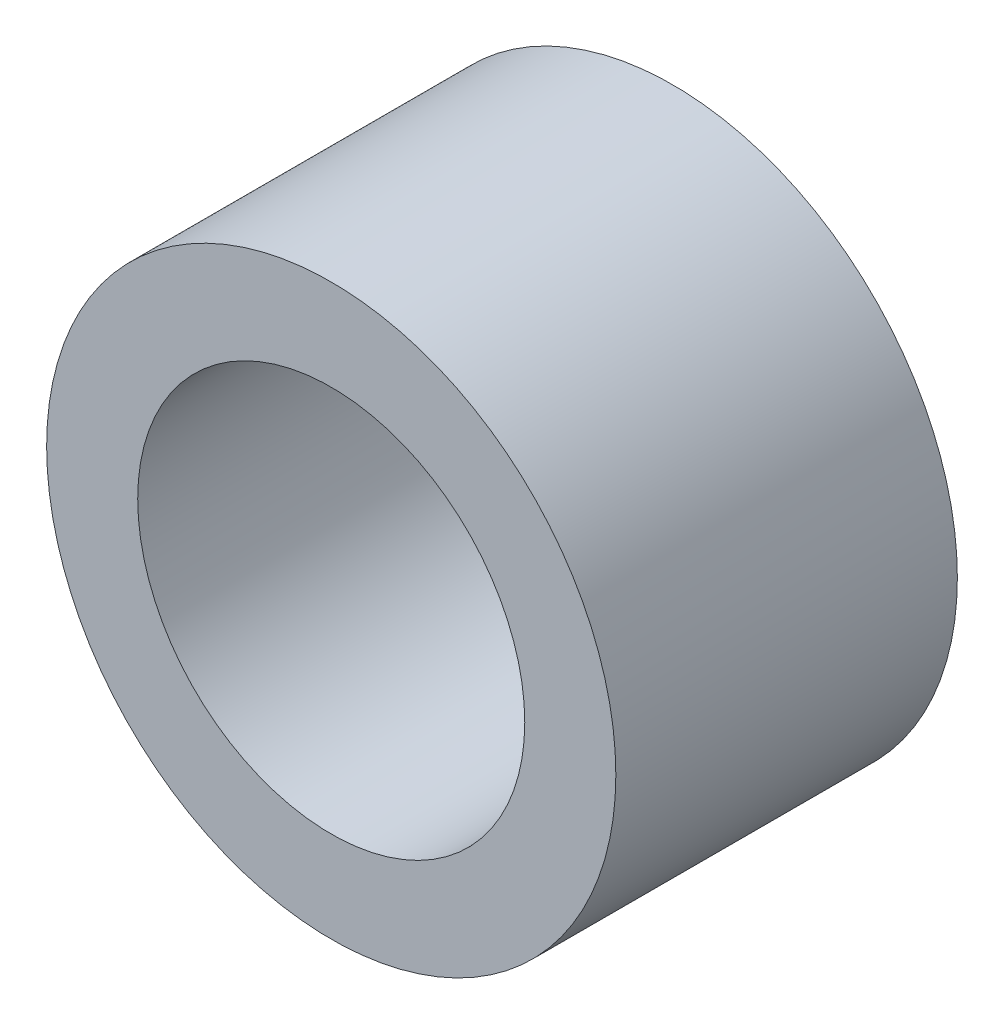
SolidWorks part; units mm, degrees
ref_plane "Front Plane" through (0, 0, 0) normal (1, 0, 0) x (0, 1, 0)
ref_plane "Top Plane" through (0, 0, 0) normal (0, 0, 1) x (0, 1, 0)
ref_plane "Right Plane" through (0, 0, 0) normal (0, 1, 0) x (-1, 0, 0)
sketch "Sketch1" plane through (0, 0, 0) normal (0, 0, 1) x (0, 1, 0)
  circle A0 centre (0, 0) radius 2.5
  dimension "D1" = 5
extrude "Boss-Extrude1" add sketch "Sketch1" along normal blind 3
sketch "Sketch2" plane through (0, 0, 3) normal (0, 0, 1) x (1, 0, 0)
  circle A0 centre (0, 0) radius 1.7
  dimension "D1" = 3.4
extrude "Cut-Extrude1" cut sketch "Sketch2" against normal through all both and the other way through all
